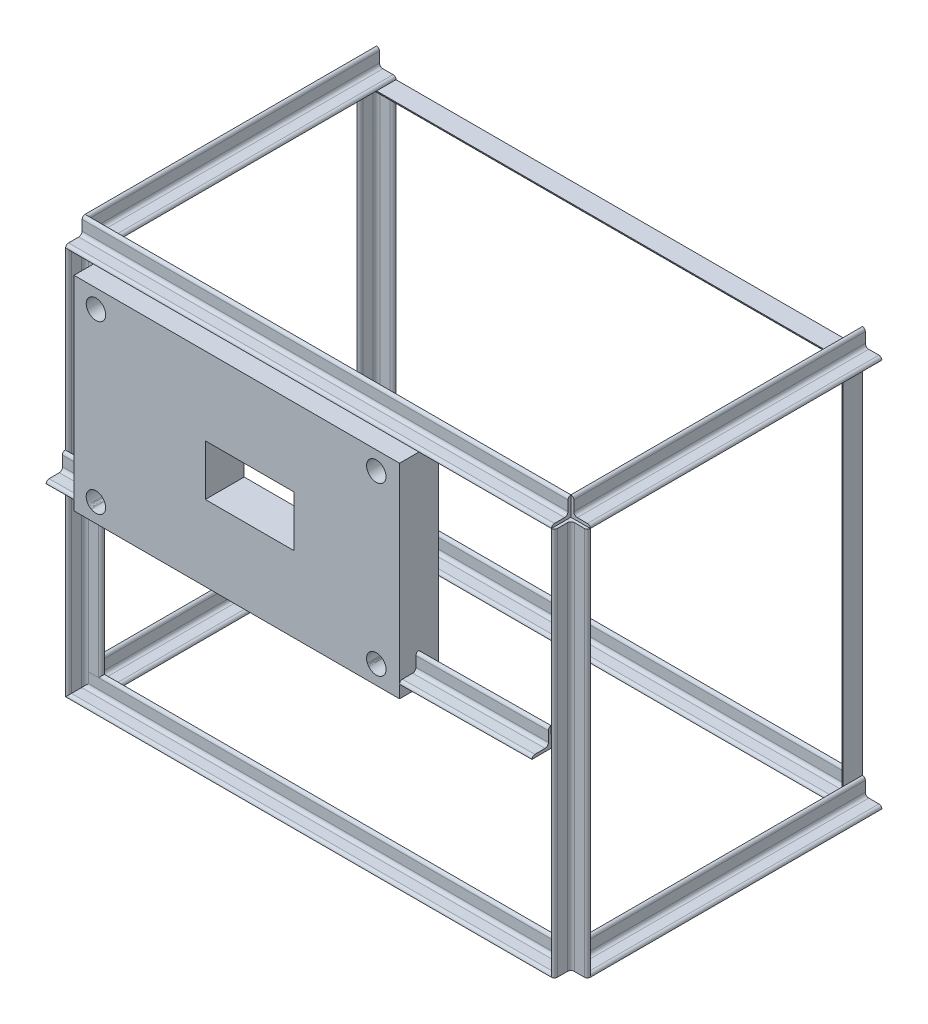
SolidWorks part; units mm, degrees
ref_plane "Front Plane" through (0, 0, 0) normal (0, 0, 1) x (1, 0, 0)
ref_plane "Top Plane" through (0, 0, 0) normal (0, 1, 0) x (1, 0, 0)
ref_plane "Right Plane" through (0, 0, 0) normal (1, 0, 0) x (0, 0, -1)
sketch "Sketch1" plane through (0, 0, 0) normal (0, 0, 1) x (1, 0, 0)
  line L0 (-250, 70.0942) -> (250, 70.0942)
  line L1 (250, -200) -> (-250, -200)
  line L2 (250, -200) -> (250, 200)
  line L3 (250, 200) -> (-250, 200)
  line L4 (-250, -200) -> (-250, 200)
  line L5 (250, -200) -> (-250, 200) construction
  line L6 (250, 200) -> (-250, -200) construction
  point P0 (0, 0)
  dimension "D1" = 500
  dimension "D2" = 400
sketch3d "3DSketch1"
  line L0 (250, 200, 0) -> (250, 200, 300)
  line L1 (250, -200, 0) -> (250, -200, 300)
  line L2 (-250, -200, 0) -> (-250, -200, 300)
  line L3 (-250, 200, 0) -> (-250, 200, 300)
  line L4 (250, 200, 300) -> (-250, 200, 300)
  line L5 (-250, 200, 300) -> (-250, -200, 300)
  line L6 (-250, -200, 300) -> (250, -200, 300)
  line L7 (250, -200, 300) -> (250, 200, 300)
  dimension "D1" = 300
  dimension "D2" = 300
  dimension "D3" = 300
  dimension "D4" = 300
sketch3d "3DSketch6"
  line L0 (250, 200, 300) -> (-250, 200, 300) construction
  line L1 (-221.3349, 200, 300) -> (113.6651, 200, 300)
  line L2 (-221.3349, 200, 300) -> (-221.3349, -10, 300)
  line L3 (-221.3349, -10, 300) -> (113.6651, -10, 300)
  line L4 (113.6651, 200, 300) -> (113.6651, -10, 300)
  dimension "D1" = 210
  dimension "D2" = 335
ref_plane "Plane6" through (0, 0, 440) normal (0, 0, 1) x (1, 0, 0)
extrude "Boss-Extrude2" add sketch "3DSketch6" along direction (0, 0, 1) on the side of the normal blind 40 separate body contours L3 L4 L1 L2
sketch "Sketch111" plane through (0, 0, 340) normal (0, 0, 1) x (1, 0, 0)
  circle A0 centre (-198.7705, 9.1831) radius 10
  circle A1 centre (-198.7705, 180.9966) radius 10
  circle A2 centre (89.7577, 180.9966) radius 10
  circle A3 centre (89.7577, 9.1831) radius 10
  point P8 (-198.7705, 180.9966)
  point P9 (89.7577, 180.9966)
  dimension "D2" = 20
sketch "Sketch113" plane through (0, 0, 340) normal (0, 0, 1) x (1, 0, 0)
  line L1 (5.0359, 67.7468) -> (-86.203, 67.7468)
  line L2 (5.0359, 67.7468) -> (5.0359, 120.0631)
  line L3 (5.0359, 120.0631) -> (-86.203, 120.0631)
  line L4 (-86.203, 67.7468) -> (-86.203, 120.0631)
  line L5 (5.0359, 67.7468) -> (-86.203, 120.0631) construction
  line L6 (5.0359, 120.0631) -> (-86.203, 67.7468) construction
  point P0 (-40.5835, 93.905)
  point P5 (-40.5835, 93.905)
extrude "Cut-Extrude2" cut sketch "Sketch113" against normal blind 40
other "Angle iron 20 X 20 X 3(1)"
ref_plane "Plane7" through (-250, 200, 300) normal (0, -1, 0) x (1, 0, 0)
sketch "Sketch128" plane through (-250, 200, 300) normal (0, -1, 0) x (1, 0, 0)
  line L0 (0, 0) -> (0, 20)
  line L1 (0, 10) -> (3, 10) construction
  line L2 (3, 17) -> (3, 6.5)
  line L3 (6.5, 3) -> (17, 3)
  line L4 (10, 3) -> (10, 0) construction
  line L5 (20, 0) -> (0, 0)
  arc A0 (20, 0) -> (17, 3) centre (17, 0) ccw
  arc A1 (0, 20) -> (3, 17) centre (0, 17) cw
  arc A2 (6.5, 3) -> (3, 6.5) centre (6.5, 6.5) cw
  point P10 (10, 0)
  point P14 (0, 10)
  point P15 (3, 10)
  point P16 (10, 3)
  point P17 (3, 20)
  point P18 (20, 3)
  point P21 (0, 0)
  dimension "D2" = 3
  dimension "D3" = 20
  dimension "Radius_1" = 3.5
  dimension "D1" = 3
other "Angle iron 20 X 20 X 3(2)"
ref_plane "Plane8" through (250, 200, 300) normal (-1, 0, 0) x (0, 0, 1)
sketch "Sketch129" plane through (250, 200, 300) normal (-1, 0, 0) x (0, 0, 1)
  line L0 (0, 0) -> (0, 20)
  line L1 (0, 10) -> (3, 10) construction
  line L2 (3, 17) -> (3, 6.5)
  line L3 (6.5, 3) -> (17, 3)
  line L4 (10, 3) -> (10, 0) construction
  line L5 (20, 0) -> (0, 0)
  arc A0 (20, 0) -> (17, 3) centre (17, 0) ccw
  arc A1 (0, 20) -> (3, 17) centre (0, 17) cw
  arc A2 (6.5, 3) -> (3, 6.5) centre (6.5, 6.5) cw
  point P10 (10, 0)
  point P14 (0, 10)
  point P15 (3, 10)
  point P16 (10, 3)
  point P17 (3, 20)
  point P18 (20, 3)
  point P21 (0, 0)
  dimension "D2" = 3
  dimension "D3" = 20
  dimension "Radius_1" = 3.5
  dimension "D1" = 3
other "Angle iron 20 X 20 X 3(3)"
ref_plane "Plane9" through (-250, 200, 0) normal (0, 0, 1) x (1, 0, 0)
sketch "Sketch130" plane through (-250, 200, 0) normal (0, 0, 1) x (1, 0, 0)
  line L0 (0, 0) -> (0, 20)
  line L1 (0, 10) -> (3, 10) construction
  line L2 (3, 17) -> (3, 6.5)
  line L3 (6.5, 3) -> (17, 3)
  line L4 (10, 3) -> (10, 0) construction
  line L5 (20, 0) -> (0, 0)
  arc A0 (20, 0) -> (17, 3) centre (17, 0) ccw
  arc A1 (0, 20) -> (3, 17) centre (0, 17) cw
  arc A2 (6.5, 3) -> (3, 6.5) centre (6.5, 6.5) cw
  point P10 (10, 0)
  point P14 (0, 10)
  point P15 (3, 10)
  point P16 (10, 3)
  point P17 (3, 20)
  point P18 (20, 3)
  point P21 (0, 0)
  dimension "D2" = 3
  dimension "D3" = 20
  dimension "Radius_1" = 3.5
  dimension "D1" = 3
other "Angle iron 20 X 20 X 3(4)"
ref_plane "Plane10" through (250, -200, 0) normal (0, 1, 0) x (-1, 0, 0)
sketch "Sketch131" plane through (250, -200, 0) normal (0, 1, 0) x (-1, 0, 0)
  line L0 (0, 0) -> (0, 20)
  line L1 (0, 10) -> (3, 10) construction
  line L2 (3, 17) -> (3, 6.5)
  line L3 (6.5, 3) -> (17, 3)
  line L4 (10, 3) -> (10, 0) construction
  line L5 (20, 0) -> (0, 0)
  arc A0 (20, 0) -> (17, 3) centre (17, 0) ccw
  arc A1 (0, 20) -> (3, 17) centre (0, 17) cw
  arc A2 (6.5, 3) -> (3, 6.5) centre (6.5, 6.5) cw
  point P10 (10, 0)
  point P14 (0, 10)
  point P15 (3, 10)
  point P16 (10, 3)
  point P17 (3, 20)
  point P18 (20, 3)
  point P21 (0, 0)
  dimension "D2" = 3
  dimension "D3" = 20
  dimension "Radius_1" = 3.5
  dimension "D1" = 3
sketch3d "3DSketch7"
  line L0 (250, 4.364, 320) -> (-250, 0, 320)
  line L1 (250, -200, 320) -> (250, 200, 320) construction
  line L2 (-250, -200, 320) -> (-250, 200, 320) construction
other "Angle iron 20 X 20 X 3(5)"
ref_plane "Plane11" through (250, 4.364, 320) normal (-1, -0.0087, 0) x (0.0001, -0.0087, 1)
sketch "Sketch132" plane through (250, 4.364, 320) normal (-1, -0.0087, 0) x (0.0001, -0.0087, 1)
  line L0 (0, 0) -> (0, 20)
  line L1 (0, 10) -> (3, 10) construction
  line L2 (3, 17) -> (3, 6.5)
  line L3 (6.5, 3) -> (17, 3)
  line L4 (10, 3) -> (10, 0) construction
  line L5 (20, 0) -> (0, 0)
  arc A0 (20, 0) -> (17, 3) centre (17, 0) ccw
  arc A1 (0, 20) -> (3, 17) centre (0, 17) cw
  arc A2 (6.5, 3) -> (3, 6.5) centre (6.5, 6.5) cw
  point P10 (10, 0)
  point P14 (0, 10)
  point P15 (3, 10)
  point P16 (10, 3)
  point P17 (3, 20)
  point P18 (20, 3)
  point P21 (0, 0)
  dimension "D2" = 3
  dimension "D3" = 20
  dimension "Radius_1" = 3.5
  dimension "D1" = 3
extrude "Cut-Extrude3" cut sketch "Sketch111" against normal blind 40
